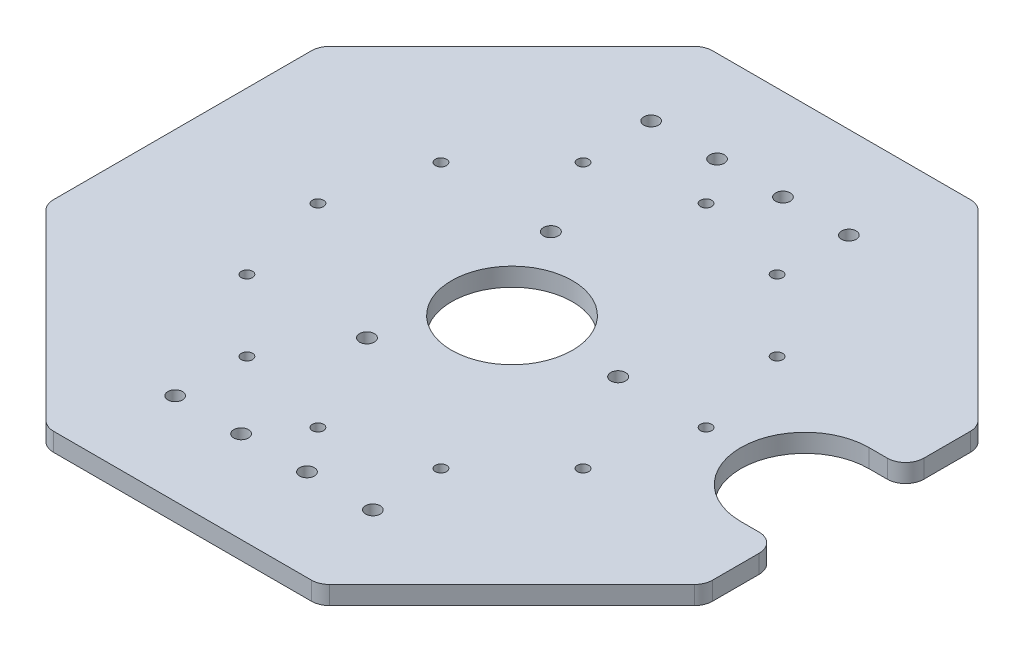
SolidWorks part; units mm, degrees
ref_plane "前视基准面" through (0, 0, 0) normal (0, 0, 1) x (1, 0, 0)
ref_plane "上视基准面" through (0, 0, 0) normal (0, 1, 0) x (1, 0, 0)
ref_plane "右视基准面" through (0, 0, 0) normal (1, 0, 0) x (0, 0, -1)
other "Configuration Table"
sketch "草图1" plane through (0, 0, 0) normal (0, 1, 0) x (1, 0, 0)
  line L0 (-90, 0) -> (90, 0) construction
  line L1 (0, 90) -> (0, -90) construction
  line L2 (-37.2792, 90) -> (37.2792, 90)
  line L3 (37.2792, 90) -> (90, 37.2792)
  line L4 (90, 37.2792) -> (90, 17.5)
  line L5 (90, -37.2792) -> (37.2792, -90)
  line L6 (-37.2792, -90) -> (37.2792, -90)
  line L7 (-37.2792, -90) -> (-90, -37.2792)
  line L8 (-90, -37.2792) -> (-90, 37.2792)
  line L9 (-90, 37.2792) -> (-37.2792, 90)
  line L10 (80, 0) -> (90, 0) construction
  line L13 (80, 17.5) -> (90, 17.5)
  line L14 (80, -17.5) -> (90, -17.5)
  line L15 (80, 0) -> (80, -17.5) construction
  line L16 (90, -17.5) -> (90, -37.2792)
  line L17 (90, 17.5) -> (90, -17.5) construction
  circle A0 centre (0, 0) radius 16.5
  circle A2 centre (29, 0) radius 2.025
  circle A3 centre (-14.5, -25.1147) radius 2.025
  circle A4 centre (-14.5, 25.1147) radius 2.025
  arc A7 (80, 17.5) -> (80, -17.5) centre (80, 0) ccw
  circle A8 centre (0, 53) radius 1.525
  circle A9 centre (26.5, 45.8993) radius 1.525
  circle A10 centre (45.8993, 26.5) radius 1.525
  circle A11 centre (53, 0) radius 1.525
  circle A12 centre (45.8993, -26.5) radius 1.525
  circle A13 centre (26.5, -45.8993) radius 1.525
  circle A14 centre (0, -53) radius 1.525
  circle A15 centre (-26.5, -45.8993) radius 1.525
  circle A16 centre (-45.8993, -26.5) radius 1.525
  circle A17 centre (-53, 0) radius 1.525
  circle A18 centre (-45.8993, 26.5) radius 1.525
  circle A19 centre (-26.5, 45.8993) radius 1.525
  point P6 (0, 0)
  point P9 (0, 90)
  point P17 (0, -90)
  point P24 (90, 0)
  point P29 (0, 0)
  point P41 (-90, 0)
  point P61 (0, 0)
  point P64 (0, 0)
  dimension "D2" = 33
  dimension "D4" = 4.05
  dimension "D9" = 3.05
  dimension "D1" = 180
  dimension "D3" = 29
  dimension "D6" = 35
  dimension "D7" = 10
  dimension "D8" = 53
  dimension "D5" = 3
  dimension "D10" = 12
extrude "凸台-拉伸1" add sketch "草图1" along normal blind 5
sketch "草图2" plane through (0, 0, 0) normal (0, -1, 0) x (1, 0, 0)
  line L0 (0, 0) -> (29, 0) construction
  circle A0 centre (19.25, 0) radius 5
  dimension "D2" = 10
  dimension "D1" = 19.25
extrude "切除-拉伸1" cut sketch "草图2" against normal blind 2
fillet "圆角1" radius 5 12 edges at (-37.2792, 2.5, -90) (37.2792, 2.5, -90) (90, 2.5, -37.2792) (90, 2.5, -17.5) (90, 2.5, 17.5) (90, 2.5, 37.2792) (-37.2792, 2.5, 90) (-90, 2.5, 37.2792) (-90, 2.5, -37.2792) (37.2792, 2.5, 90) (16.0471, 1, 3.8394) (16.0471, 1, -3.8394)
sketch "草图3" plane through (0, 5, 0) normal (0, 1, 0) x (1, 0, 0)
  line L0 (0, 0) -> (-90, 0) construction
  line L1 (-90, 35.2082) -> (-90, -35.2082) construction
  line L2 (27, -65) -> (9, -65) construction
  line L3 (0, 0) -> (0, -90) construction
  line L4 (-35.2082, -90) -> (35.2082, -90) construction
  circle A0 centre (27, -65) radius 2
  circle A1 centre (9, -65) radius 2
  circle A2 centre (-27, -65) radius 2
  circle A3 centre (-9, -65) radius 2
  circle A4 centre (27, 65) radius 2
  circle A5 centre (9, 65) radius 2
  circle A6 centre (-9, 65) radius 2
  circle A7 centre (-27, 65) radius 2
  dimension "D2" = 4
  dimension "D1" = 18
  dimension "D3" = 9
  dimension "D4" = 65
extrude "切除-拉伸2" cut sketch "草图3" against normal blind 10
